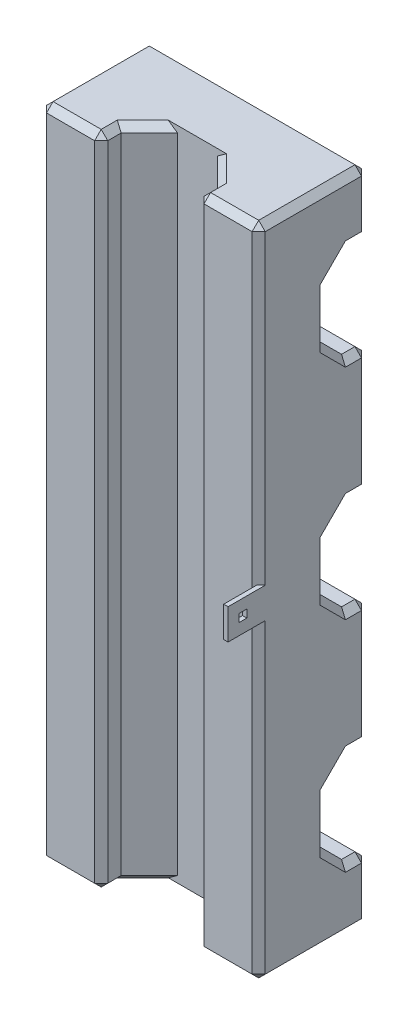
SolidWorks part; units mm, degrees
ref_plane "Front" through (0, 0, 0) normal (0, 0, 1) x (1, 0, 0)
ref_plane "Top" through (0, 0, 0) normal (0, 1, 0) x (1, 0, 0)
ref_plane "Right" through (0, 0, 0) normal (1, 0, 0) x (0, 0, -1)
sketch "Sketch1" plane through (0, 0, 0) normal (0, 0, 1) x (1, 0, 0)
  line L1 (0, 0) -> (50, 0)
  line L2 (0, 0) -> (0, 150)
  line L3 (0, 150) -> (50, 150)
  line L4 (50, 0) -> (50, 150)
  dimension "D1" = 50
  dimension "D2" = 150
extrude "Boss-Extrude1" add sketch "Sketch1" along normal blind 25
sketch "Sketch2" plane through (0, 0, 0) normal (0, -1, 0) x (1, 0, 0)
  line L0 (0, 25) -> (50, 25) construction
  line L1 (29.5563, 36) -> (20.4437, 36)
  line L2 (20.4437, 36) -> (14, 29.5563)
  line L3 (14, 29.5563) -> (14, 20.4437)
  line L4 (14, 20.4437) -> (20.4437, 14)
  line L5 (20.4437, 14) -> (29.5563, 14)
  line L6 (29.5563, 14) -> (36, 20.4437)
  line L7 (36, 20.4437) -> (36, 29.5563)
  line L8 (36, 29.5563) -> (29.5563, 36)
  circle A0 centre (25, 25) radius 11 construction
  dimension "D1" = 22
extrude "Cut-Extrude1" cut sketch "Sketch2" against normal through all
sketch "Sketch3" plane through (50, 0, 0) normal (1, 0, 0) x (0, 0, -1)
  line L0 (0, 0) -> (0, 150) construction
  line L1 (-4.5563, 36) -> (-11, 29.5563)
  line L2 (-11, 29.5563) -> (-11, 20.4437)
  line L3 (-11, 20.4437) -> (-4.5563, 14)
  line L4 (-4.5563, 14) -> (4.5563, 14)
  line L5 (4.5563, 14) -> (11, 20.4437)
  line L6 (11, 20.4437) -> (11, 29.5563)
  line L7 (11, 29.5563) -> (4.5563, 36)
  line L8 (4.5563, 36) -> (-4.5563, 36)
  line L9 (-25, 0) -> (0, 0) construction
  circle A0 centre (0, 25) radius 11 construction
  dimension "D1" = 25
  dimension "D2" = 22
extrude "Cut-Extrude2" cut sketch "Sketch3" against normal through all
pattern_linear "LPattern1" count 3 spacing 50 along (0, 1, 0) of "Cut-Extrude2"
chamfer "Chamfer1" distance 1.5 angle 45 60 edges at (0, 67.2218, 7.7782) (0, 64, 2.2782) (0, 32.7782, 7.7782) (0, 36, 2.2782) (50, 32.7782, 7.7782) (25, 36, 0) (50, 36, 2.2782) (50, 50, 0) (50, 67.2218, 7.7782) (50, 64, 2.2782) (0, 50, 0) (25, 64, 0) (0, 117.2218, 7.7782) (0, 114, 2.2782) (50, 82.7782, 7.7782) (50, 86, 2.2782) (0, 82.7782, 7.7782) (0, 86, 2.2782) (25, 86, 0) (0, 100, 0) (25, 114, 0) (50, 100, 0) (50, 114, 2.2782) (50, 117.2218, 7.7782) (0, 17.2218, 7.7782) (0, 14, 2.2782) (0, 7, 0) (25, 14, 0) (50, 17.2218, 7.7782) (50, 14, 2.2782) (50, 7, 0) (25, 136, 0) (0, 132.7782, 7.7782) (0, 136, 2.2782) (50, 132.7782, 7.7782) (50, 136, 2.2782) (0, 143, 0) (0, 150, 12.5) (25, 150, 0) (50, 143, 0) (50, 150, 12.5) (43, 0, 25) (32.7782, 0, 17.2218) (36, 0, 22.7218) (36, 75, 25) (32.7782, 150, 17.2218) (36, 150, 22.7218) (43, 150, 25) (50, 75, 25) (50, 0, 12.5) (25, 0, 0) (0, 0, 12.5) (7, 0, 25) (0, 75, 25) (7, 150, 25) (17.2218, 150, 17.2218) (14, 150, 22.7218) (14, 75, 25) (14, 0, 22.7218) (17.2218, 0, 17.2218)
sketch "Sketch4" plane through (0, 0, 25) normal (0, 0, 1) x (1, 0, 0)
  line L0 (50, 148.5) -> (50, 1.5) construction
  line L1 (50, 78.5) -> (49, 78.5)
  line L2 (50, 78.5) -> (50, 71.5)
  line L3 (50, 71.5) -> (49, 71.5)
  line L4 (49, 78.5) -> (49, 71.5)
  point P6 (50, 75)
  dimension "D1" = 7
  dimension "D2" = 1
extrude "Boss-Extrude2" add sketch "Sketch4" along normal blind 7 and the other way blind 10
sketch "Sketch5" plane through (50, 0, 0) normal (1, 0, 0) x (0, 0, -1)
  line L0 (-32, 71.5) -> (-32, 78.5) construction
  line L1 (-29.5, 74.1) -> (-27.7, 74.1)
  line L2 (-29.5, 74.1) -> (-29.5, 75.9)
  line L3 (-29.5, 75.9) -> (-27.7, 75.9)
  line L4 (-27.7, 74.1) -> (-27.7, 75.9)
  line L5 (-29.5, 75) -> (-32, 75) construction
  dimension "D1" = 1.8
  dimension "D2" = 2.5
extrude "Cut-Extrude3" cut sketch "Sketch5" against normal blind 7
